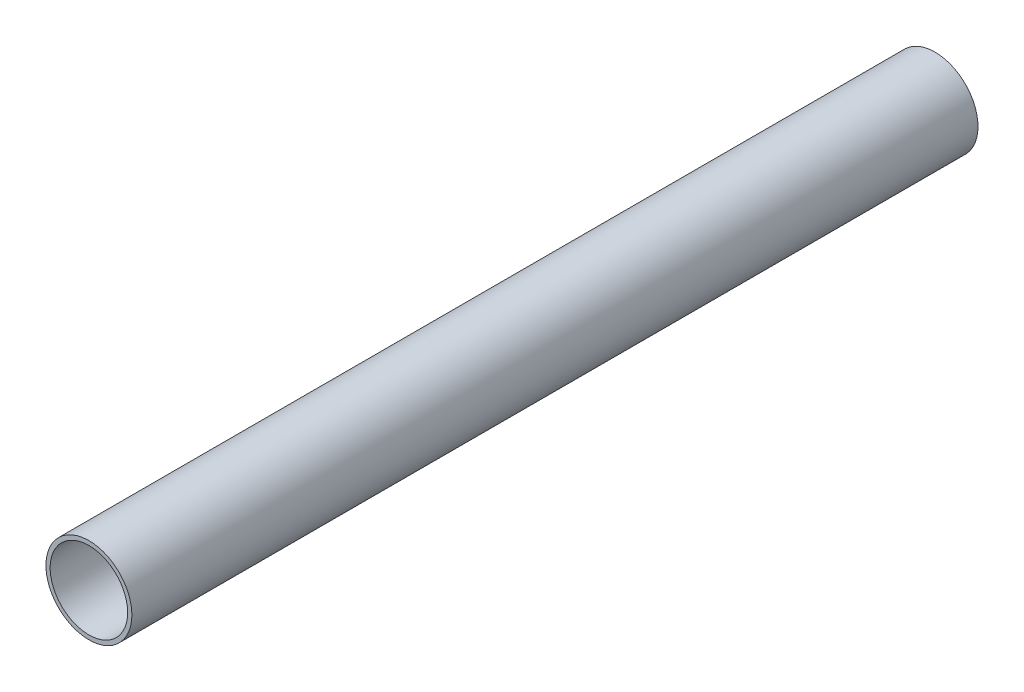
SolidWorks part; units mm, degrees
ref_plane "Alzado" through (0, 0, 0) normal (0, 0, 1) x (1, 0, 0)
ref_plane "Planta" through (0, 0, 0) normal (0, 1, 0) x (1, 0, 0)
ref_plane "Vista lateral" through (0, 0, 0) normal (1, 0, 0) x (0, 0, -1)
sketch "Croquis1" plane through (0, 0, 0) normal (0, 0, 1) x (1, 0, 0)
  circle A0 centre (0, 0) radius 101.6
  circle A1 centre (0, 0) radius 91.6
  dimension "D1" = 203.2
  dimension "D2" = 10
extrude "Saliente-Extruir1" add sketch "Croquis1" along normal blind 2000
